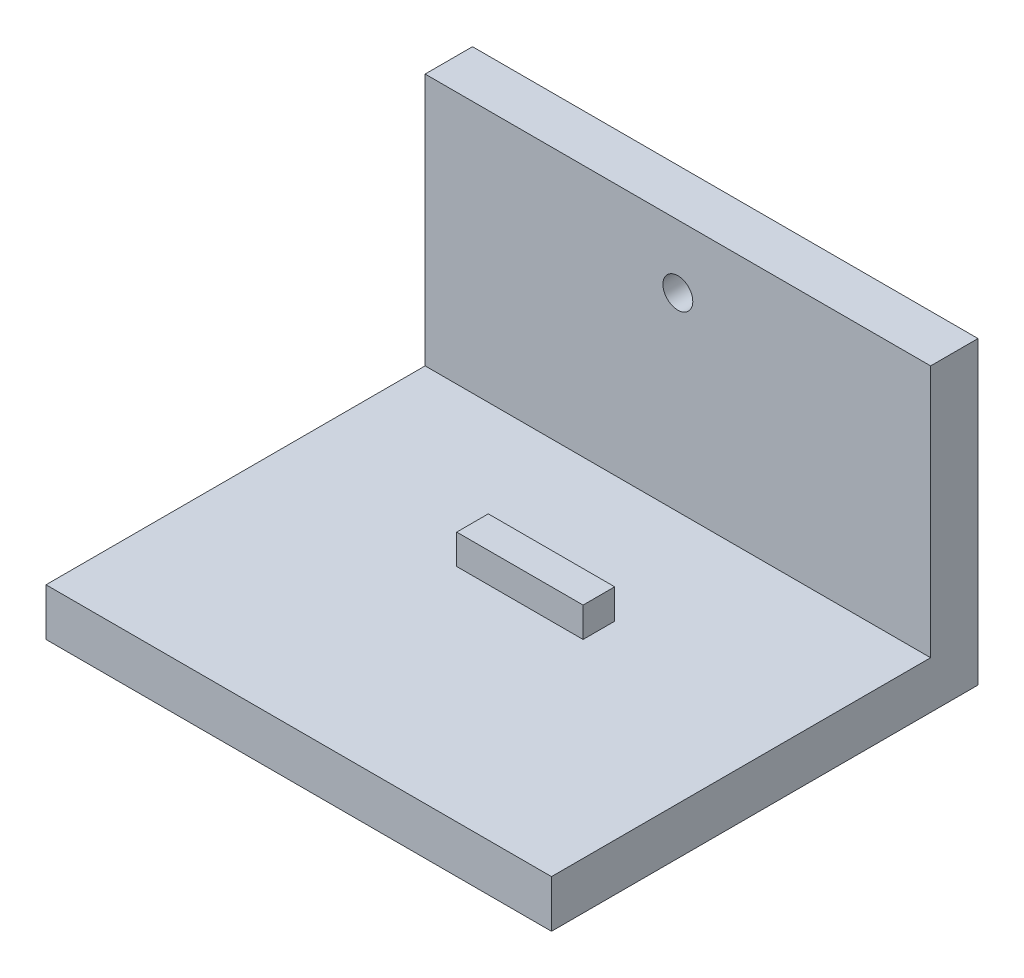
SolidWorks part; units mm, degrees
ref_plane "Front Plane" through (0, 0, 0) normal (0, 0, 1) x (1, 0, 0)
ref_plane "Top Plane" through (0, 0, 0) normal (0, 1, 0) x (1, 0, 0)
ref_plane "Right Plane" through (0, 0, 0) normal (1, 0, 0) x (0, 0, -1)
sketch "Sketch1" plane through (0, 0, 0) normal (1, 0, 0) x (0, 0, -1)
  line L0 (0, 0) -> (-42.8625, 0)
  line L1 (-42.8625, 0) -> (-42.8625, 4.7625)
  line L2 (-42.8625, 4.7625) -> (-4.7625, 4.7625)
  line L3 (-4.7625, 4.7625) -> (-4.7625, 30.1625)
  line L4 (-4.7625, 30.1625) -> (0, 30.1625)
  line L5 (0, 30.1625) -> (0, 0)
  dimension "D1" = 38.1
  dimension "D2" = 25.4
  dimension "D3" = 4.7625
extrude "Boss-Extrude1" add sketch "Sketch1" along normal blind 50.8
sketch "Sketch2" plane through (0, 4.7625, 0) normal (0, 1, 0) x (1, 0, 0)
  line L0 (50.8, -42.8625) -> (0, -42.8625) construction
  line L1 (19.05, -20.6375) -> (31.75, -20.6375)
  line L2 (19.05, -20.6375) -> (19.05, -17.4625)
  line L3 (19.05, -17.4625) -> (31.75, -17.4625)
  line L4 (31.75, -20.6375) -> (31.75, -17.4625)
  line L7 (50.8, -4.7625) -> (0, -4.7625) construction
  point P4 (25.4, -20.6375)
  point P7 (25.4, -42.8625)
  dimension "D1" = 3.175
  dimension "D2" = 12.7
  dimension "D3" = 12.7
extrude "Boss-Extrude2" add sketch "Sketch2" along normal blind 2.9972
sketch "Sketch3" plane through (0, 0, 4.7625) normal (0, 0, 1) x (1, 0, 0)
  line L0 (50.8, 30.1625) -> (0, 30.1625) construction
  line L1 (50.8, 4.7625) -> (0, 4.7625) construction
  circle A0 centre (25.4, 23.8125) radius 1.5
  point P5 (25.4, 30.1625)
  dimension "D1" = 3
  dimension "D2" = 19.05
extrude "Cut-Extrude1" cut sketch "Sketch3" against normal through all
